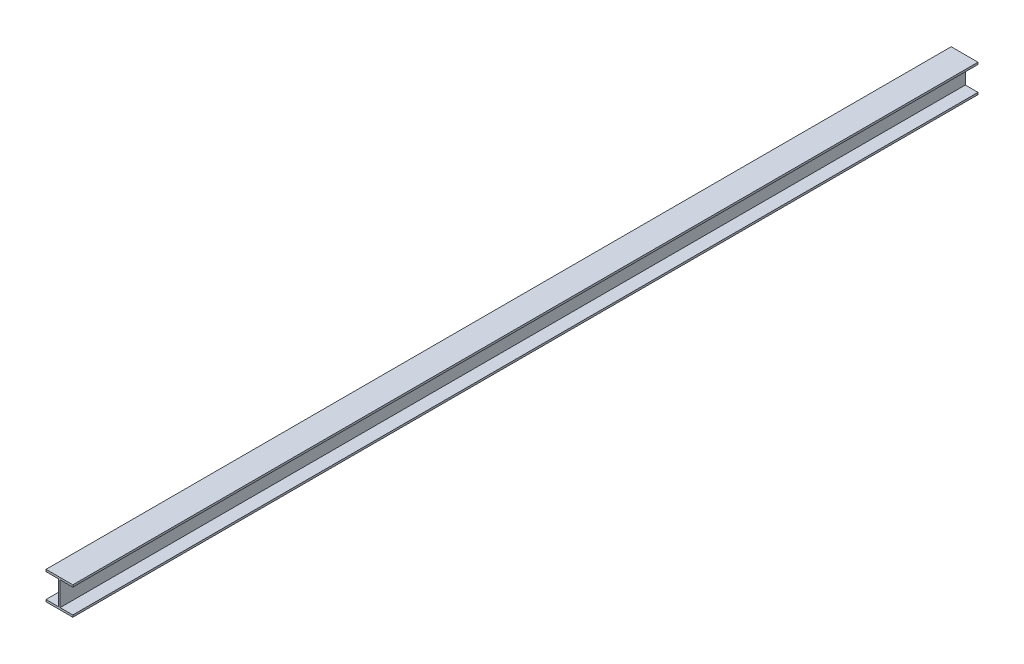
SolidWorks part; units mm, degrees
material "ASTM A992 Steel"
ref_plane "Front" through (0, 0, 0) normal (0, 0, 1) x (1, 0, 0)
ref_plane "Top" through (0, 0, 0) normal (0, 1, 0) x (1, 0, 0)
ref_plane "Right" through (0, 0, 0) normal (1, 0, 0) x (0, 0, -1)
sketch "Sketch1" plane through (0, 0, 0) normal (0, 0, 1) x (1, 0, 0)
  line L0 (0, -0.0002) -> (154.432, -0.0002)
  line L1 (154.432, -0.0002) -> (154.432, -11.5572)
  line L2 (154.432, -11.5572) -> (81.28, -11.5572)
  line L3 (81.28, -11.5572) -> (81.28, -150.4952)
  line L4 (81.28, -150.4952) -> (154.432, -150.4952)
  line L5 (154.432, -150.4952) -> (154.432, -162.0522)
  line L6 (154.432, -162.0522) -> (0, -162.0522)
  line L7 (0, -162.0522) -> (0, -150.4952)
  line L8 (0, -150.4952) -> (73.152, -150.4952)
  line L9 (73.152, -150.4952) -> (73.152, -11.5572)
  line L10 (73.152, -11.5572) -> (0, -11.5572)
  line L11 (0, -11.5572) -> (0, -0.0002)
  line L12 (77.216, -0.0002) -> (77.216, -162.0522) construction
  point P15 (154.432, -156.2737)
  dimension "D1" = 8.128
  dimension "D2" = 11.557
  dimension "D3" = 11.557
  dimension "D4" = 11.557
  dimension "D5" = 162.052
  dimension "D6" = 4.064
  dimension "D7" = 77.216
  dimension "D8" = 77.216
extrude "Boss-Extrude1" add sketch "Sketch1" along normal blind 5214.4
sketch "Sketch2" plane through (0, -162.0522, 0) normal (0, -1, 0) x (1, 0, 0)
  line L0 (0, 5214.4) -> (0, 0) construction
  line L1 (154.432, 5214.4) -> (154.432, 0) construction
  line L3 (154.432, 2607.2) -> (154.432, 2759.6)
  line L4 (154.432, 2759.6) -> (-279.5172, 2759.6)
  line L5 (-279.5172, 2607.2) -> (-279.5172, 2759.6)
  line L8 (154.432, 2607.2) -> (154.432, 2454.8)
  line L9 (154.432, 2454.8) -> (-279.5172, 2454.8)
  line L10 (-279.5172, 2607.2) -> (-279.5172, 2454.8)
  point P0 (0, 2607.2)
  dimension "D1" = 152.4
  dimension "D2" = 152.4
split line "Split Line1"
